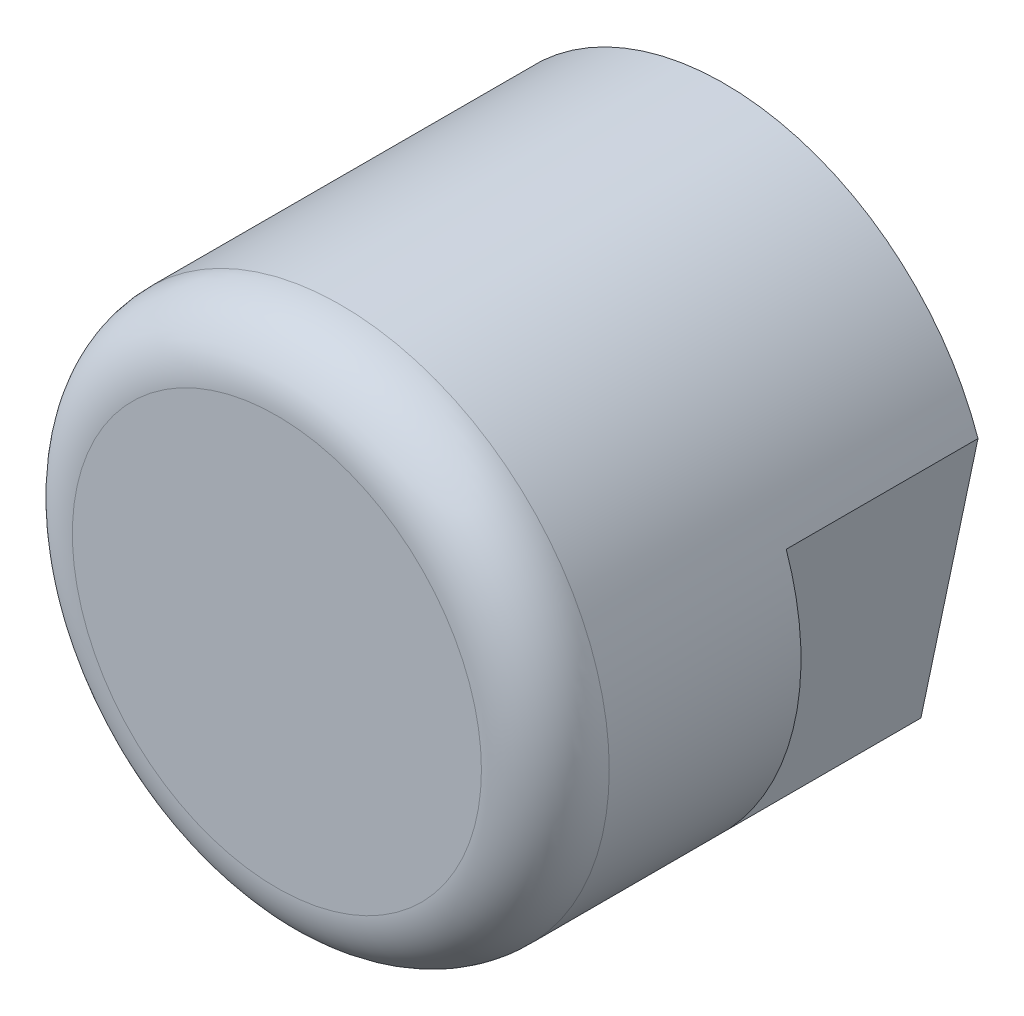
SolidWorks part; units mm, degrees
ref_plane "Front Plane" through (0, 0, 0) normal (0, 0, 1) x (1, 0, 0)
ref_plane "Top Plane" through (0, 0, 0) normal (0, 1, 0) x (1, 0, 0)
ref_plane "Right Plane" through (0, 0, 0) normal (1, 0, 0) x (0, 0, -1)
sketch "Sketch1" plane through (0, 0, 0) normal (0, 0, 1) x (1, 0, 0)
  circle A0 centre (0, 0) radius 21
extrude "Boss-Extrude1" add sketch "Sketch1" along normal blind 40
sketch "Sketch2" plane through (0, 0, 0) normal (0, 0, -1) x (-1, 0, 0)
  circle A1 centre (0, 0) radius 10
  circle A2 centre (0, 0) radius 9
  circle M1 centre (0, 0) radius 21
extrude "Cut-Extrude1" cut sketch "Sketch2" against normal blind 5 contours A1 M1
sketch "Sketch3" plane through (0, 0, 0) normal (0, 0, -1) x (-1, 0, 0)
  circle A0 centre (0, 0) radius 4.5
sketch "Sketch4" plane through (0, 0, 5) normal (0, 0, -1) x (-1, 0, 0)
  line L0 (15.3793, 14.2996) -> (19.8453, -6.8677)
  circle A0 centre (0, 0) radius 21 construction
  arc A1 (19.8453, -6.8677) -> (15.3793, 14.2996) centre (0, 0) ccw
  dimension "D1" = 18
extrude "Cut-Extrude2" cut sketch "Sketch4" against normal blind 15
ref_plane "Plane1" through (0, 0, 0) normal (-0.9785, 0.2064, 0) x (0, 0, 1)
mirror "Mirror1" about plane through (0, 0, 0) normal (-0.9785, 0.2064, 0) of "Cut-Extrude2"
fillet "Fillet1" radius 5 1 edges at (21, 0, 40)
extrude "Cut-Extrude3" cut sketch "Sketch3" against normal blind 10
